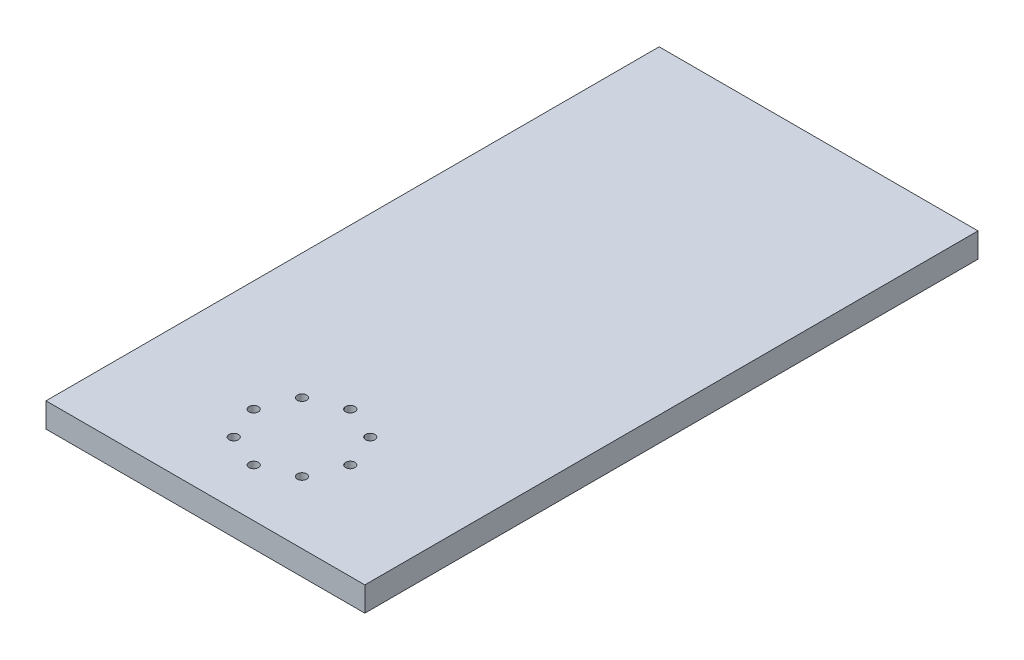
SolidWorks part; units mm, degrees
material "6061 Alloy"
ref_plane "Front Plane" through (0, 0, 0) normal (0, 0, 1) x (1, 0, 0)
ref_plane "Top Plane" through (0, 0, 0) normal (0, 1, 0) x (1, 0, 0)
ref_plane "Right Plane" through (0, 0, 0) normal (1, 0, 0) x (0, 0, -1)
sketch "Sketch1" plane through (0, 0, 0) normal (0, 1, 0) x (1, 0, 0)
  line L1 (-127, -177.8) -> (127, -177.8)
  line L2 (-127, -177.8) -> (-127, 177.8)
  line L3 (-127, 177.8) -> (127, 177.8)
  line L4 (127, -177.8) -> (127, 177.8)
  line L5 (-127, -177.8) -> (127, 177.8) construction
  line L6 (-127, 177.8) -> (127, -177.8) construction
  point P0 (0, 0)
  dimension "D1" = 254
  dimension "D2" = 355.6
extrude "Base_extrude" add sketch "Sketch1" along normal blind 12.7
sketch "Sketch6" plane through (0, 12.7, 0) normal (0, 1, 0) x (1, 0, 0)
  line L0 (0, 177.8) -> (0, -177.8) construction
  line L1 (127, 177.8) -> (-127, 177.8) construction
  line L2 (-127, -177.8) -> (127, -177.8) construction
  line L4 (-67, 177.8) -> (98.1, 177.8)
  line L5 (-67, 177.8) -> (-67, -139.7)
  line L6 (-67, -139.7) -> (98.1, -139.7)
  line L7 (98.1, 177.8) -> (98.1, -139.7)
  line L8 (-67, 177.8) -> (98.1, -139.7) construction
  line L9 (-67, -139.7) -> (98.1, 177.8) construction
  line L10 (-127, 177.8) -> (-127, -177.8) construction
  point P6 (15.55, 19.05)
  dimension "D1" = 60
  dimension "D2" = 165.1
  dimension "317.5" = 317.5
extrude "Cut_to_size" cut sketch "Sketch6" against normal through all flip side to cut
sketch "Sketch2" [suppressed] plane through (0, 12.7, 0) normal (0, 1, 0) x (1, 0, 0)
  line L0 (36.0312, 94) -> (36.0312, 47) construction
  circle A0 centre (0, 0) radius 29.21
  point P0 (0, 0)
  point P1 (-45, 0)
  dimension "D5" = 58.42
  dimension "50" = 45
  dimension "D2" = 36.0312
  dimension "D3" = 47
  dimension "55" = 47
extrude "Motor_Clearance" [suppressed] cut sketch "Sketch2" against normal through all
sketch "Sketch4" [suppressed] plane through (0, 12.7, 0) normal (0, 1, 0) x (1, 0, 0)
  line L0 (25.019, 0) -> (-25.019, 0) construction
  line L1 (0, 25.019) -> (0, -25.019) construction
  line L2 (25.019, 25.019) -> (-25.019, 25.019) construction
  line L3 (25.019, 25.019) -> (25.019, -25.019) construction
  line L4 (25.019, -25.019) -> (-25.019, -25.019) construction
  line L5 (-25.019, -25.019) -> (-25.019, 25.019) construction
  circle A0 centre (25.019, 25.019) radius 2.286
  circle A1 centre (25.019, -25.019) radius 2.286
  circle A2 centre (-25.019, -25.019) radius 2.286
  circle A3 centre (-25.019, 25.019) radius 2.286
  dimension "D1" = 4.572
  dimension "D2" = 4.572
  dimension "D3" = 4.572
  dimension "D4" = 4.572
  dimension "D5" = 50.038
  dimension "D6" = 50.038
extrude "Motor_Mount" [suppressed] cut sketch "Sketch4" against normal through all
sketch "Sketch5" [suppressed] plane through (0, 12.7, 0) normal (0, 1, 0) x (1, 0, 0)
  circle A0 centre (-45, 0) radius 2.5
  dimension "D1" = 5
extrude "PinA" [suppressed] cut sketch "Sketch5" against normal through all
sketch "Sketch7" [suppressed] plane through (0, 0, 0) normal (0, -1, 0) x (1, 0, 0)
  line L1 (33.655, -33.655) -> (-33.655, -33.655)
  line L2 (33.655, -33.655) -> (33.655, 33.655)
  line L3 (33.655, 33.655) -> (-33.655, 33.655)
  line L4 (-33.655, -33.655) -> (-33.655, 33.655)
  line L5 (33.655, -33.655) -> (-33.655, 33.655) construction
  line L6 (33.655, 33.655) -> (-33.655, -33.655) construction
  point P0 (0, 0)
  dimension "D1" = 67.31
  dimension "D2" = 67.31
extrude "Motor_height" [suppressed] cut sketch "Sketch7" against normal blind 6.35
sketch "Lin_bearing_mount" [suppressed] plane through (0, 12.7, 0) normal (0, 1, 0) x (1, 0, 0)
  line L0 (9.1072, 157.5022) -> (9.1072, 127.3778) construction
  line L1 (62.9552, 157.5022) -> (62.9552, 127.3778) construction
  circle A0 centre (62.9552, 127.3778) radius 2.2809
  circle A1 centre (62.9552, 157.5022) radius 2.286
  circle A2 centre (9.1072, 157.5022) radius 2.286
  circle A3 centre (9.1072, 127.3778) radius 2.286
  dimension "D1" = 4.572
  dimension "D2" = 4.5618
  dimension "D3" = 4.572
  dimension "D4" = 4.572
extrude "Linear_Bearing" [suppressed] cut sketch "Lin_bearing_mount" against normal through all
sketch "Version2" [suppressed] plane through (0, 12.7, 0) normal (0, 1, 0) x (1, 0, 0)
  line L0 (15.55, 177.8) -> (15.55, -139.7) construction
  line L1 (98.1, 177.8) -> (-67, 177.8) construction
  line L2 (-67, -139.7) -> (98.1, -139.7) construction
  line L3 (98.1, 19.05) -> (-67, 19.05) construction
  line L4 (98.1, -139.7) -> (98.1, 177.8) construction
  line L5 (-67, 177.8) -> (-67, -139.7) construction
  line L6 (53.65, 117.506) -> (53.65, 64.9031) construction
  circle A0 centre (-22.55, 82.55) radius 29.21
  circle A1 centre (2.469, 107.569) radius 2.286
  circle A2 centre (2.469, 57.531) radius 2.286
  circle A3 centre (-47.569, 107.569) radius 2.286
  circle A4 centre (-47.569, 57.531) radius 2.286
  point P14 (28.25, -44.45)
  point P17 (26.6625, 74.6125)
  dimension "D1" = 58.42
  dimension "D12" = 4.572
  dimension "D2" = 127
  dimension "D3" = 50.8
  dimension "D4" = 76.2
  dimension "D5" = 63.5
  dimension "D6" = 76.2
  dimension "D7" = 7.9375
  dimension "D8" = 49.2125
  dimension "D9" = 50.038
  dimension "D10" = 25.019
  dimension "D11" = 50.038
  dimension "D13" = 25.019
extrude "Cut-Extrude2" [suppressed] cut sketch "Version2" against normal through all
sketch "Sketch9" [suppressed] plane through (0, 0, 0) normal (0, -1, 0) x (-1, 0, 0)
  line L1 (-11.105, 116.205) -> (56.205, 116.205)
  line L2 (-11.105, 116.205) -> (-11.105, 48.895)
  line L3 (-11.105, 48.895) -> (56.205, 48.895)
  line L4 (56.205, 116.205) -> (56.205, 48.895)
  line L5 (-11.105, 116.205) -> (56.205, 48.895) construction
  line L6 (-11.105, 48.895) -> (56.205, 116.205) construction
  circle A0 centre (22.55, 82.55) radius 29.21 construction
  point P0 (22.55, 82.55)
  dimension "D1" = 67.31
  dimension "D2" = 67.31
extrude "Motor_square_cutout" [suppressed] cut sketch "Sketch9" against normal blind 4.7473
sketch "Sketch10" [suppressed] plane through (0, 12.7, 0) normal (0, 1, 0) x (1, 0, 0)
  line L0 (-67, 19.05) -> (98.1, 19.05) construction
  line L1 (-67, 177.8) -> (-67, -139.7) construction
  line L2 (98.1, -139.7) -> (98.1, 177.8) construction
  line L3 (15.55, 177.8) -> (15.55, -139.7) construction
  line L4 (98.1, 177.8) -> (-67, 177.8) construction
  line L5 (-67, -139.7) -> (98.1, -139.7) construction
  circle A0 centre (-22.55, 82.55) radius 29.21 construction
  circle A1 centre (27.45, -47.45) radius 2.0828
  point P12 (27.45, -47.45)
  dimension "D1" = 50
  dimension "D2" = 130
  dimension "D3" = 4.1656
extrude "Pin_C_loc" [suppressed] cut sketch "Sketch10" against normal through all
sketch "Sketch11" [suppressed] plane through (0, 12.7, 0) normal (0, 1, 0) x (1, 0, 0)
  line L0 (15.55, 177.8) -> (15.55, -139.7) construction
  line L1 (98.1, 177.8) -> (-67, 177.8) construction
  line L2 (-67, -139.7) -> (98.1, -139.7) construction
  line L3 (98.1, 19.05) -> (-67, 19.05) construction
  line L4 (98.1, -139.7) -> (98.1, 177.8) construction
  line L5 (-67, 177.8) -> (-67, -139.7) construction
  line L6 (84.4375, 109.5375) -> (84.4375, 80.9625) construction
  line L7 (30.4625, 109.5375) -> (30.4625, 80.9625) construction
  line L8 (84.4375, 95.25) -> (30.4625, 95.25) construction
  line L9 (57.45, 108.9032) -> (57.45, 81.5968) construction
  circle A0 centre (-22.55, 82.55) radius 29.21 construction
  circle A1 centre (30.4625, 80.9625) radius 2.0828
  circle A2 centre (84.4375, 80.9625) radius 2.0828
  circle A3 centre (30.4625, 109.5375) radius 2.0828
  circle A4 centre (84.4375, 109.5375) radius 2.0828
  point P12 (30.4625, 80.9625)
  point P15 (30.4625, 80.9625)
  point P28 (57.45, 95.25)
  dimension "D1" = 12.7
  dimension "D2" = 53.975
  dimension "D3" = 4.1656
  dimension "D4" = 28.575
  dimension "D5" = 28.575
  dimension "D6" = 80
extrude "Bearing_hole_loc" [suppressed] cut sketch "Sketch11" against normal through all
sketch "Sketch12" plane through (0, 12.7, 0) normal (0, 1, 0) x (1, 0, 0)
  line L0 (15.55, 177.8) -> (15.55, -139.7) construction
  line L1 (98.1, 177.8) -> (-67, 177.8) construction
  line L2 (-67, -139.7) -> (98.1, -139.7) construction
  line L3 (33.2277, -72.0223) -> (-2.1277, -107.3777) construction
  line L4 (33.2277, -107.3777) -> (-2.1277, -72.0223) construction
  circle A0 centre (15.55, -89.7) radius 25
  circle A1 centre (33.2277, -107.3777) radius 2.413
  circle A2 centre (40.55, -89.7) radius 2.413
  circle A3 centre (33.2277, -72.0223) radius 2.413
  circle A4 centre (15.55, -64.7) radius 2.413
  circle A5 centre (-2.1277, -72.0223) radius 2.413
  circle A6 centre (-9.45, -89.7) radius 2.413
  circle A7 centre (-2.1277, -107.3777) radius 2.413
  circle A8 centre (15.55, -114.7) radius 2.413
  dimension "D1" = 50
  dimension "D3" = 4.826
  dimension "D2" = 50
  dimension "D4" = 45
  dimension "D5" = 45
extrude "Cut-Extrude3" cut sketch "Sketch12" against normal through all contours A0 A3 | A0 A3 | A0 A2 | A0 A2 | A0 A1 | A0 A1 | A0 A8 | A0 A8 | A0 A7 | A0 A7 | A0 A6 | A0 A6 | A0 A5 | A0 A5 | A0 A4 | A0 A4
equation "\"D6@Sketch4\"=\"D5@Sketch4\""
equation "\"D11@Version2\"=\"D9@Version2\""
